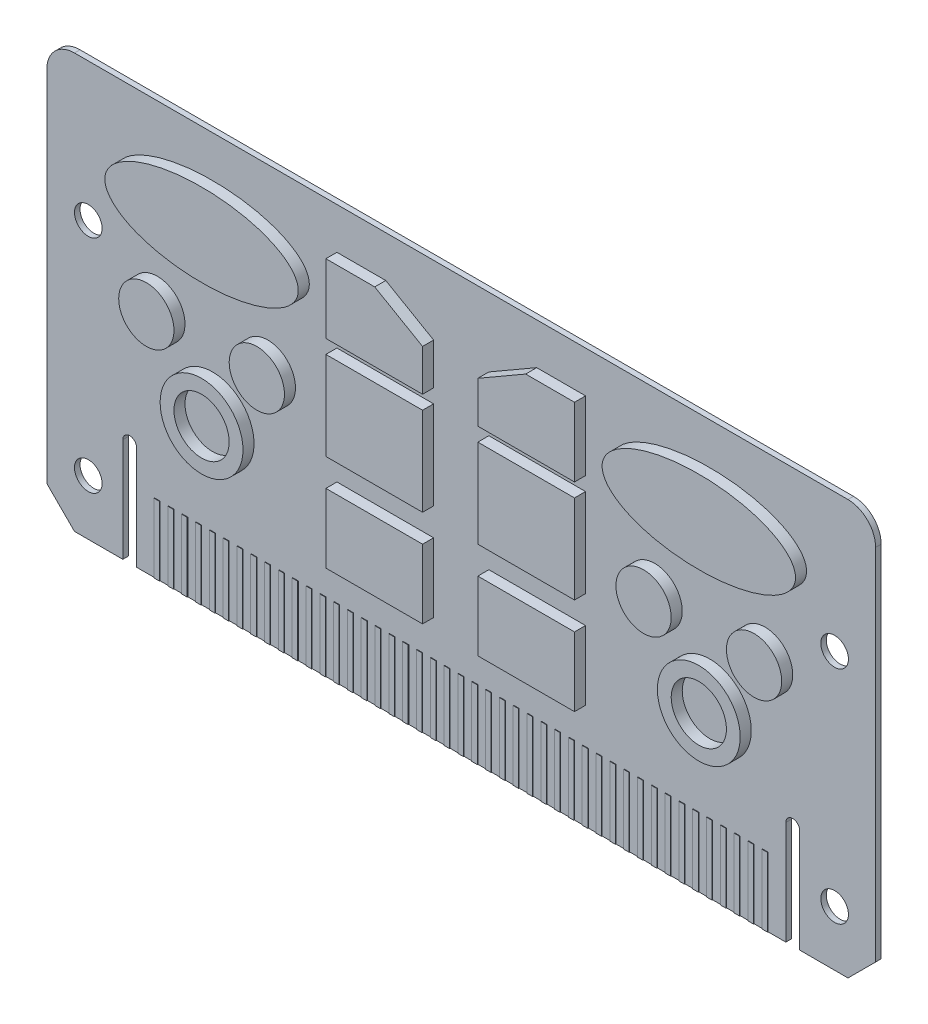
SolidWorks part; units mm, degrees
ref_plane "Front Plane" through (0, 0, 0) normal (0, 0, 1) x (1, 0, 0)
ref_plane "Top Plane" through (0, 0, 0) normal (0, 1, 0) x (1, 0, 0)
ref_plane "Right Plane" through (0, 0, 0) normal (1, 0, 0) x (0, 0, -1)
sketch "Sketch4" plane through (0, 0, 0) normal (0, 0, 1) x (1, 0, 0)
  line L1 (-300, 150) -> (0, 150)
  line L2 (-300, 150) -> (-300, 0)
  line L3 (-300, 0) -> (0, 0)
  line L4 (0, 150) -> (0, 0)
  dimension "D1" = 300
  dimension "D2" = 150
extrude "PCB Base" add sketch "Sketch4" along normal mid plane 2 contours L2 L1 L4 L3
sketch "Sketch5" plane through (0, 0, 1) normal (0, 0, 1) x (1, 0, 0)
  line L0 (-300, 150) -> (-300, 0) construction
  line L2 (-300, 0) -> (0, 0) construction
  line L3 (0, 150) -> (0, 0) construction
  line L4 (-160, 38) -> (-195, 38)
  line L5 (-160, 38) -> (-160, 63)
  line L6 (-160, 63) -> (-195, 63)
  line L7 (-195, 38) -> (-195, 63)
  line L8 (-195, 73) -> (-160, 73)
  line L9 (-195, 73) -> (-195, 105)
  line L10 (-195, 105) -> (-160, 105)
  line L11 (-160, 73) -> (-160, 105)
  line L12 (-195, 110) -> (-160, 110)
  line L13 (-195, 110) -> (-195, 135)
  line L14 (-195, 135) -> (-177.3205, 135)
  line L15 (-160, 110) -> (-160, 125)
  line L16 (-177.3205, 135) -> (-160, 125)
  line L17 (-150, 150) -> (-150, 0) construction
  line L18 (-300, 150) -> (0, 150) construction
  line L19 (-140, 110) -> (-140, 125)
  line L20 (-140, 38) -> (-140, 63)
  line L21 (-140, 73) -> (-140, 105)
  line L22 (-122.6795, 135) -> (-140, 125)
  line L23 (-105, 135) -> (-122.6795, 135)
  line L24 (-105, 110) -> (-105, 135)
  line L25 (-105, 110) -> (-140, 110)
  line L26 (-105, 105) -> (-140, 105)
  line L27 (-105, 73) -> (-105, 105)
  line L28 (-105, 73) -> (-140, 73)
  line L29 (-105, 38) -> (-105, 63)
  line L30 (-140, 63) -> (-105, 63)
  line L31 (-140, 38) -> (-105, 38)
  circle A0 centre (-260, 85) radius 10
  circle A1 centre (-220, 85) radius 10
  circle A2 centre (-240, 60) radius 15
  circle A3 centre (-240, 60) radius 10
  circle A4 centre (-60, 60) radius 10
  circle A5 centre (-60, 60) radius 15
  circle A6 centre (-80, 85) radius 10
  circle A7 centre (-40, 85) radius 10
  ellipse E0 centre (-240, 120) end of major axis (-275, 120) minor radius 15
  ellipse E1 centre (-60, 120) end of major axis (-25, 120) minor radius 15
  dimension "D1" = 20
  dimension "D5" = 5
  dimension "D8" = 30
  dimension "D2" = 40
  dimension "D3" = 40
  dimension "D4" = 85
  dimension "D6" = 60
  dimension "D7" = 60
  dimension "D9" = 70
  dimension "D10" = 30
  dimension "D11" = 60
  dimension "D12" = 120
  dimension "D13" = 38
  dimension "D14" = 25
  dimension "D15" = 73
  dimension "D16" = 32
  dimension "D17" = 110
  dimension "D18" = 135
  dimension "D19" = 195
  dimension "D20" = 160
  dimension "D21" = 125
  dimension "D22" = 120
extrude "PCB Chips" add sketch "Sketch5" along normal blind 4
mirror "Mirror1" about plane through (0, 0, 0) normal (0, 0, 1) of "PCB Chips"
sketch "Sketch6" plane through (0, 0, 1) normal (0, 0, 1) x (1, 0, 0)
  line L0 (-272.5, 37.5) -> (-272.5, 0)
  line L1 (-300, 0) -> (0, 0) construction
  line L2 (-267.5, 37.5) -> (-267.5, 0)
  line L3 (-300, 150) -> (-300, 0) construction
  line L4 (-30, 0) -> (-30, 37.5) construction
  line L5 (-32.5, 0) -> (-32.5, 37.5)
  line L6 (-27.5, 0) -> (-27.5, 37.5)
  line L7 (-150, 150) -> (-150, 0) construction
  line L8 (-300, 150) -> (0, 150) construction
  line L9 (-272.5, 0) -> (-267.5, 0)
  arc A0 (-272.5, 37.5) -> (-267.5, 37.5) centre (-270, 37.5) cw
  arc A1 (-32.5, 0) -> (-27.5, 0) centre (-30, 0) ccw
  arc A2 (-27.5, 37.5) -> (-32.5, 37.5) centre (-30, 37.5) ccw
  point P7 (-30, 18.75)
  dimension "D4" = 2.5
  dimension "D1" = 5
  dimension "D2" = 27.5
  dimension "D3" = 40
  dimension "D5" = 5
extrude "Slot Cut" cut sketch "Sketch6" against normal blind 10
hole_wizard "Ø10.0mm Dowel Hole1" positions "Sketch7" profile "Sketch8" hole size "Ø10.0" standard "ANSI Metric"
sketch "Sketch7" plane through (0, 0, 1) normal (0, 0, 1) x (1, 0, 0)
  line L0 (-300, 0) -> (-272.5, 0) construction
  line L1 (-300, 150) -> (-300, 0) construction
  point P7 (-285, 100)
  point P9 (-285, 20)
  point P11 (-14.8385, 20)
  point P13 (-14.8385, 100)
  point P21 (0, 0)
  point P22 (0, 0)
  point P23 (0, 0)
  dimension "D1" = 20
  dimension "D2" = 100
  dimension "D3" = 15
sketch "Sketch8" plane through (-285, 100, 1) normal (1, 0, 0) x (0, -1, 0)
  line L0 (0, 0) -> (0, 13.0043)
  line L1 (0, 13.0043) -> (5, 10)
  line L2 (5, 10) -> (5, 0)
  line L5 (5, 0) -> (0, 0)
  line L10 (0, 13.0043) -> (-5, 10) construction
  line L11 (0, -6.35) -> (0, 107.95) construction
  dimension "Hole Dia." = 10
  dimension "Hole Depth" = 10
  dimension "Drill Angle" = 118
sketch "Sketch11" plane through (0, 0, 1) normal (0, 0, 1) x (1, 0, 0)
  line L0 (-267.5, 0) -> (-32.5, 0) construction
  line L1 (-261, 0) -> (-259, 0)
  line L2 (-261, 0) -> (-261, 25)
  line L3 (-261, 25) -> (-259, 25)
  line L4 (-259, 0) -> (-259, 25)
  dimension "D1" = 25
  dimension "D2" = 2
  dimension "D3" = 6.5
extrude "Contact" add sketch "Sketch11" along normal blind 0.2
pattern_linear "Contact Pattern" count 45 spacing 5 along (1, 0, 0) of "Contact"
chamfer "Chamfer1" distance 10 angle 45 2 edges at (-300, 0, 0) (0, 0, 0)
fillet "Fillet1" radius 10 2 edges at (-300, 150, 0) (0, 150, 0)
